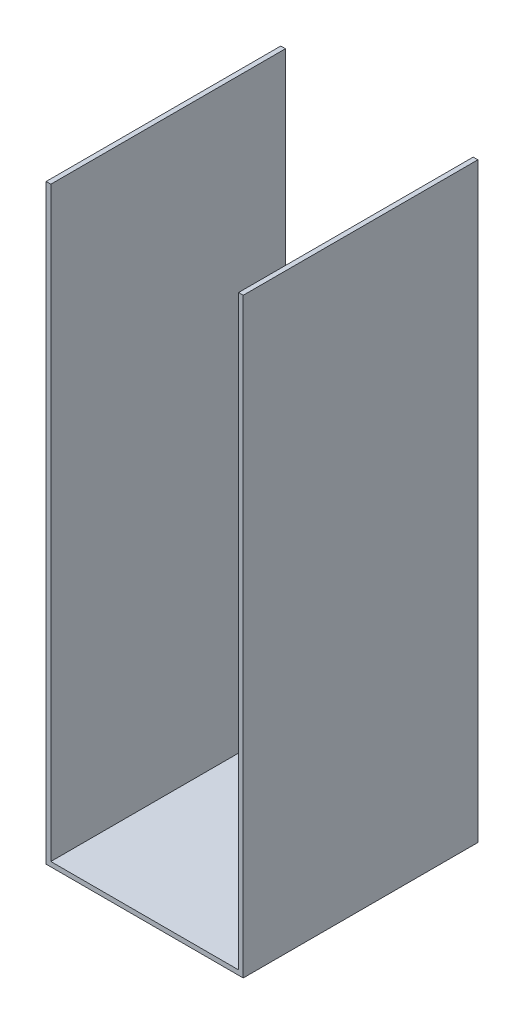
SolidWorks part; units mm, degrees
ref_plane "Front Plane" through (0, 0, 0) normal (0, 0, 1) x (1, 0, 0)
ref_plane "Top Plane" through (0, 0, 0) normal (0, 1, 0) x (1, 0, 0)
ref_plane "Right Plane" through (0, 0, 0) normal (1, 0, 0) x (0, 0, -1)
sketch "Sketch2" plane through (0, 0, 0) normal (0, 0, 1) x (1, 0, 0)
  line L0 (0, 0) -> (0, -25000)
  line L1 (0, -25000) -> (8000, -25000)
  line L2 (8000, -25000) -> (8000, 0)
  line L3 (-200, 0) -> (-200, -25200)
  line L4 (-200, -25200) -> (8200, -25200)
  line L5 (8200, -25200) -> (8200, 0)
  line L6 (-200, 0) -> (0, 0)
  line L7 (8000, 0) -> (8200, 0)
extrude "Boss-Extrude1" add sketch "Sketch2" against normal blind 10000
